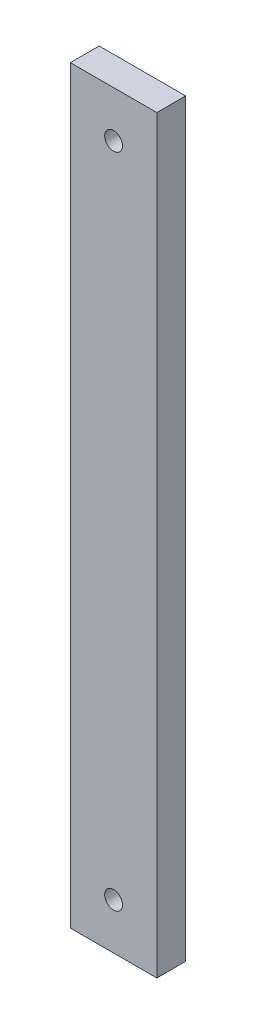
SolidWorks part; units mm, degrees
ref_plane "Front" through (0, 0, 0) normal (0, 0, 1) x (1, 0, 0)
ref_plane "Top" through (0, 0, 0) normal (0, 1, 0) x (1, 0, 0)
ref_plane "Right" through (0, 0, 0) normal (1, 0, 0) x (0, 0, -1)
sketch "Sketch1" plane through (0, 0, 0) normal (0, 0, 1) x (1, 0, 0)
  line L1 (-7.5, -65) -> (7.5, -65)
  line L2 (-7.5, -65) -> (-7.5, 65)
  line L3 (-7.5, 65) -> (7.5, 65)
  line L4 (7.5, -65) -> (7.5, 65)
  line L5 (-7.5, -65) -> (7.5, 65) construction
  line L6 (-7.5, 65) -> (7.5, -65) construction
  circle A0 centre (0, 57) radius 1.55
  circle A1 centre (0, -57) radius 1.55
  point P0 (0, 0)
  dimension "D3" = 3.1
  dimension "D4" = 3.1
  dimension "D1" = 130
  dimension "D2" = 15
  dimension "D5" = 8
  dimension "D6" = 8
extrude "Boss-Extrude1" add sketch "Sketch1" along normal blind 5
